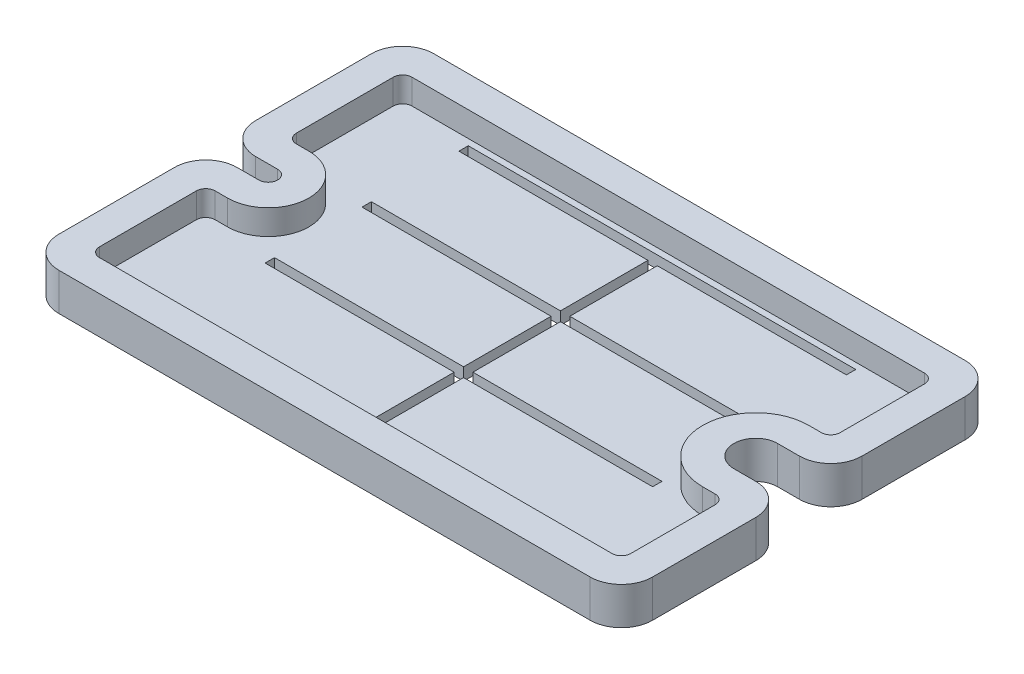
SolidWorks part; units mm, degrees
ref_plane "Front Plane" through (0, 0, 0) normal (0, 0, 1) x (1, 0, 0)
ref_plane "Top Plane" through (0, 0, 0) normal (0, 1, 0) x (1, 0, 0)
ref_plane "Right Plane" through (0, 0, 0) normal (1, 0, 0) x (0, 0, -1)
sketch "Sketch1" plane through (0, 0, 0) normal (0, 1, 0) x (1, 0, 0)
  line L0 (47.5, 0) -> (47.5, 60) construction
  line L1 (0, 0) -> (95, 0)
  line L2 (0, 0) -> (0, 60)
  line L3 (0, 60) -> (95, 60)
  line L4 (95, 0) -> (95, 60)
  line L5 (47.5, 3.5) -> (78, 3.5) construction
  line L6 (47.5, 3.5) -> (17, 3.5) construction
  line L7 (47.5, 21) -> (78, 21) construction
  line L8 (47.5, 21) -> (17, 21) construction
  line L9 (47.5, 38.5) -> (78, 38.5) construction
  line L10 (47.5, 38.5) -> (17, 38.5) construction
  line L11 (47.5, 56) -> (78, 56) construction
  line L12 (47.5, 56) -> (17, 56) construction
  line L13 (17, 3.5) -> (17, 21) construction
  line L14 (17, 21) -> (17, 38.5) construction
  line L15 (17, 38.5) -> (17, 56) construction
  dimension "D1" = 95
  dimension "D2" = 60
  dimension "D3" = 30.5
  dimension "D4" = 17.5
  dimension "D5" = 3.5
extrude "Boss-Extrude1" add sketch "Sketch1" along normal blind 6
sketch "Sketch6" plane through (0, 0, 0) normal (0, -1, 0) x (1, 0, 0)
  line L0 (0, -30) -> (95, -30) construction
  line L1 (0, -60) -> (0, 0) construction
  line L2 (95, 0) -> (95, -60) construction
  line L3 (95, -30) -> (86.5, -30) construction
  line L4 (0, -30) -> (8.5, -30) construction
  line L5 (10, -30) -> (83, -30) construction
  circle A0 centre (86.5, -30) radius 3.5
  circle A2 centre (8.5, -30) radius 1.5
  dimension "D2" = 8.5
  dimension "D3" = 3
  dimension "D4" = 7
  dimension "D5" = 73
  dimension "D1" = 8.5
extrude "Cut-Extrude3" cut sketch "Sketch6" against normal through all
sketch "Sketch2" plane through (0, 6, 0) normal (0, 1, 0) x (-1, 0, 0)
  line L5 (0, 0) -> (-95, 0) construction
  line L6 (-95, -60) -> (0, -60) construction
  line L7 (0, -60) -> (0, 0) construction
  line L8 (-95, 0) -> (-95, -60) construction
  line L9 (-8.5, -36.5) -> (-5, -36.5)
  line L10 (-8.5, -23.5) -> (-5, -23.5)
  line L11 (-86.5, -38.5) -> (-90, -38.5)
  line L12 (-86.5, -21.5) -> (-90, -21.5)
  line L13 (-5, -5) -> (-90, -5)
  line L14 (-90, -5) -> (-90, -21.5)
  line L15 (-90, -55) -> (-5, -55)
  line L16 (-5, -55) -> (-5, -36.5)
  line L17 (-90, -38.5) -> (-90, -55)
  line L20 (-5, -23.5) -> (-5, -5)
  arc A0 (-8.5, -23.5) -> (-8.5, -36.5) centre (-8.5, -30) ccw
  arc A1 (-86.5, -38.5) -> (-86.5, -21.5) centre (-86.5, -30) ccw
  circle A2 centre (-86.5, -30) radius 3.5 construction
  circle A3 centre (-8.5, -30) radius 1.5 construction
  dimension "D5" = 5
  dimension "D6" = 5
  dimension "D1" = 5
  dimension "D2" = 5
  dimension "D3" = 5
  dimension "D4" = 5
  dimension "D7" = 5
extrude "Cut-Extrude1" cut sketch "Sketch2" against normal blind 4
sketch "Sketch4" plane through (0, 0, 0) normal (0, -1, 0) x (1, 0, 0)
  line L0 (47.5, -60) -> (47.5, 0) construction
  line L1 (47.5, -53.25) -> (78.5, -53.25) construction
  line L2 (47.5, -53.25) -> (16.5, -53.25) construction
  line L3 (47.5, -37.75) -> (78.5, -37.75) construction
  line L4 (47.5, -37.75) -> (16.5, -37.75) construction
  line L5 (47.5, -22.25) -> (78.5, -22.25) construction
  line L6 (47.5, -22.25) -> (16.5, -22.25) construction
  line L7 (47.5, -6.75) -> (78.5, -6.75) construction
  line L8 (47.5, -6.75) -> (16.5, -6.75) construction
  line L9 (16.5, -53.25) -> (16.5, -37.75) construction
  line L10 (16.5, -37.75) -> (16.5, -22.25) construction
  line L11 (16.5, -22.25) -> (16.5, -6.75) construction
  line L12 (0, 0) -> (95, 0) construction
  line L13 (95, -60) -> (0, -60) construction
  dimension "D1" = 31
  dimension "D2" = 15.5
  dimension "D3" = 6.75
  dimension "D4" = 6.75
sketch "Sketch5" plane through (0, 0, 0) normal (0, -1, 0) x (1, 0, 0)
  line L0 (46.75, -37) -> (46.75, -23)
  line L1 (48.25, -37) -> (48.25, -23)
  line L2 (46.75, -52.5) -> (46.75, -38.5)
  line L3 (48.25, -52.5) -> (48.25, -38.5)
  line L4 (47.5, -60) -> (47.5, 0) construction
  line L5 (46.75, -14.5) -> (48.25, -14.5) construction
  line L6 (78.5, -6) -> (47.5, -6)
  line L7 (47.5, -6) -> (16.5, -6)
  line L8 (16.5, -6) -> (16.5, -7.5)
  line L9 (16.5, -21.5) -> (16.5, -23)
  line L10 (47.5, -7.6462) -> (46.75, -7.6462) construction
  line L11 (47.5, -7.6462) -> (48.25, -7.6462) construction
  line L12 (16.5, -23) -> (46.75, -23)
  line L13 (48.25, -23) -> (78.5, -23)
  line L16 (16.5, -21.5) -> (46.75, -21.5)
  line L17 (48.25, -21.5) -> (78.5, -21.5)
  line L18 (16.5, -37) -> (16.5, -38.5)
  line L21 (78.5, -7.5) -> (48.25, -7.5)
  line L22 (46.75, -7.5) -> (16.5, -7.5)
  line L23 (16.5, -52.5) -> (16.5, -54)
  line L24 (78.5, -52.5) -> (78.5, -54)
  line L27 (16.5, -38.5) -> (46.75, -38.5)
  line L28 (48.25, -38.5) -> (78.5, -38.5)
  line L31 (16.5, -37) -> (46.75, -37)
  line L32 (48.25, -37) -> (78.5, -37)
  line L33 (78.5, -37) -> (78.5, -38.5)
  line L34 (46.75, -21.5) -> (46.75, -7.5)
  line L37 (16.5, -54) -> (47.5, -54)
  line L38 (47.5, -54) -> (78.5, -54)
  line L41 (16.5, -52.5) -> (46.75, -52.5)
  line L42 (48.25, -52.5) -> (78.5, -52.5)
  line L43 (78.5, -21.5) -> (78.5, -23)
  line L44 (78.5, -6) -> (78.5, -7.5)
  line L47 (48.25, -21.5) -> (48.25, -7.5)
  dimension "D1" = 1.5
extrude "Cut-Extrude2" cut sketch "Sketch5" against normal through all
fillet "Fillet3" radius 1.5 1 edges at (90, 4, -55)
sketch "Sketch7" plane through (0, 6, 0) normal (0, 1, 0) x (-1, 0, 0)
  line L0 (0, -60) -> (0, 0) construction
  line L1 (0, -31.5) -> (-8.5, -31.5)
  line L2 (0, -31.5) -> (0, -28.5)
  line L3 (0, -28.5) -> (-8.5, -28.5)
  line L4 (-8.5, -31.5) -> (-8.5, -28.5)
  line L5 (-95, 0) -> (-95, -60) construction
  line L6 (-95, -33.5) -> (-86.5, -33.5)
  line L7 (-95, -33.5) -> (-95, -26.5)
  line L8 (-95, -26.5) -> (-86.5, -26.5)
  line L9 (-86.5, -33.5) -> (-86.5, -26.5)
  line L10 (0, -60) -> (0, -30) construction
  line L11 (0, 0) -> (0, -30) construction
  line L12 (-95, -30) -> (-95, 0) construction
  line L15 (-95, -60) -> (-95, -30) construction
  circle A0 centre (-86.5, -30) radius 3.5 construction
  dimension "D1" = 3
  dimension "D2" = 7
extrude "Cut-Extrude4" cut sketch "Sketch7" against normal through all
fillet "Fillet4" radius 5 8 edges at (95, 3, -33.5) (0, 3, 0) (0, 3, -28.5) (0, 3, -31.5) (0, 3, -60) (95, 3, -60) (95, 3, -26.5) (95, 3, 0)
fillet "Fillet5" radius 1.5 7 edges at (90, 4, -38.5) (90, 4, -5) (90, 4, -21.5) (5, 4, -5) (5, 4, -36.5) (5, 4, -23.5) (5, 4, -55)
